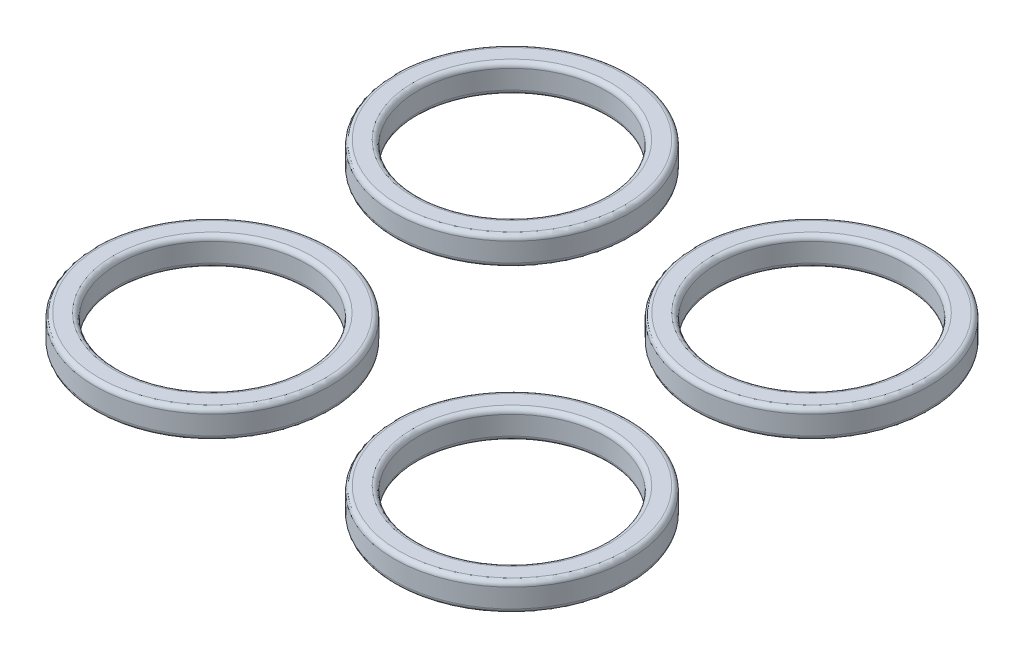
SolidWorks part; units mm, degrees
ref_plane "Front Plane" through (0, 0, 0) normal (0, 0, 1) x (1, 0, 0)
ref_plane "Top Plane" through (0, 0, 0) normal (0, 1, 0) x (1, 0, 0)
ref_plane "Right Plane" through (0, 0, 0) normal (1, 0, 0) x (0, 0, -1)
sketch "Sketch1" plane through (0, 0, 0) normal (0, 1, 0) x (1, 0, 0)
  line L1 (-159.099, -159.099) -> (159.099, -159.099) construction
  line L2 (-159.099, -159.099) -> (-159.099, 159.099) construction
  line L3 (-159.099, 159.099) -> (159.099, 159.099) construction
  line L4 (159.099, -159.099) -> (159.099, 159.099) construction
  line L5 (-159.099, -159.099) -> (159.099, 159.099) construction
  line L6 (-159.099, 159.099) -> (159.099, -159.099) construction
  circle A0 centre (-159.099, 159.099) radius 125
  circle A1 centre (159.099, 159.099) radius 125
  circle A2 centre (-159.099, -159.099) radius 125
  circle A3 centre (159.099, -159.099) radius 125
  circle A4 centre (-159.099, 159.099) radius 100
  circle A5 centre (159.099, 159.099) radius 100
  circle A6 centre (159.099, -159.099) radius 100
  circle A7 centre (-159.099, -159.099) radius 100
  point P0 (0, 0)
  dimension "D3" = 250
  dimension "D4" = 200
  dimension "D1" = 450
  dimension "D2" = 45
extrude "Boss-Extrude1" add sketch "Sketch1" along normal blind 30
fillet "Fillet1" radius 5 4 edges at (-159.099, 0, 284.099) (-159.099, 30, 284.099) (-159.099, 0, 259.099) (-159.099, 30, 259.099)
fillet "Fillet2" radius 5 4 edges at (159.099, 0, 284.099) (159.099, 30, 284.099) (159.099, 0, 259.099) (159.099, 30, 259.099)
fillet "Fillet3" radius 5 4 edges at (-159.099, 0, -34.099) (-159.099, 30, -34.099) (-159.099, 0, -59.099) (-159.099, 30, -59.099)
fillet "Fillet4" radius 5 4 edges at (159.099, 0, -34.099) (159.099, 30, -34.099) (159.099, 0, -59.099) (159.099, 30, -59.099)
